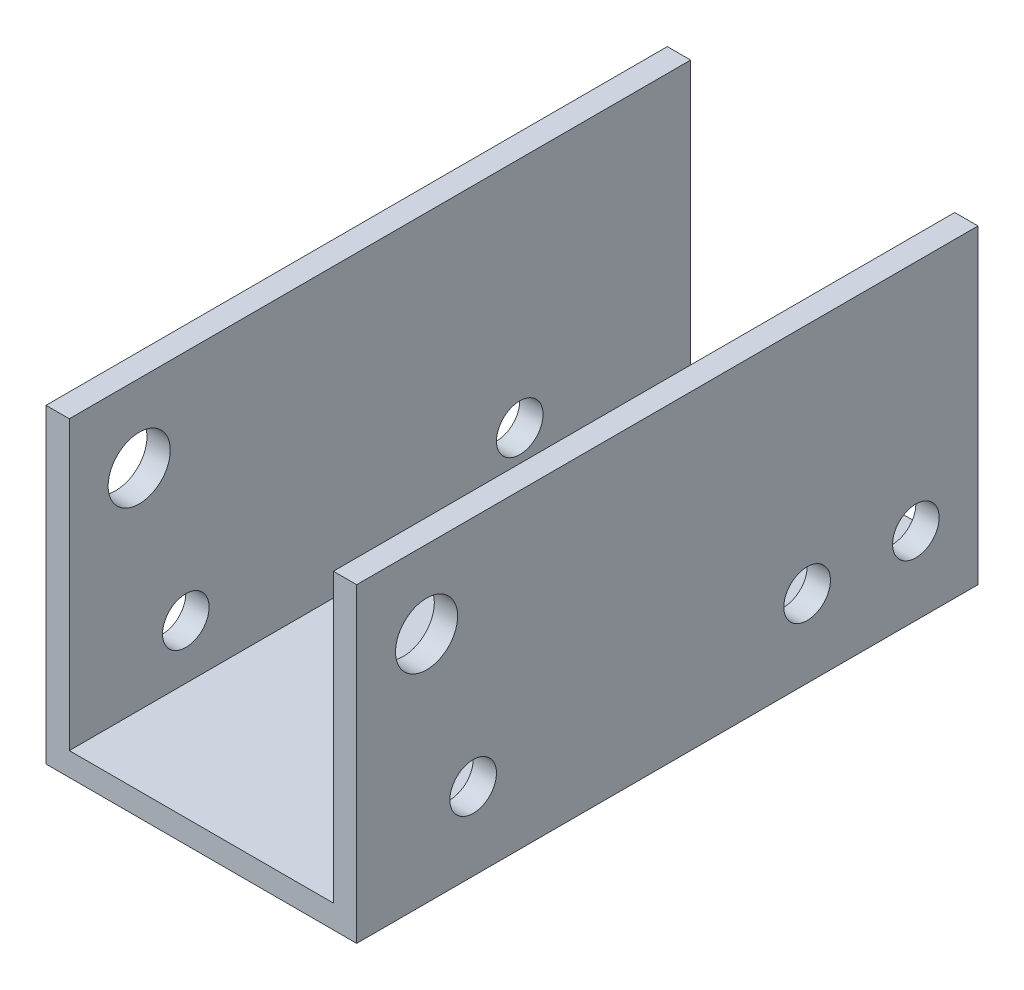
SolidWorks part; units mm, degrees
ref_plane "Plan de face" through (0, 0, 0) normal (0, 0, 1) x (1, 0, 0)
ref_plane "Plan de dessus" through (0, 0, 0) normal (0, 1, 0) x (1, 0, 0)
ref_plane "Plan de droite" through (0, 0, 0) normal (1, 0, 0) x (0, 0, -1)
sketch "Esquisse1" plane through (0, 0, 0) normal (0, 0, 1) x (1, 0, 0)
  line L0 (-8.9048, 18.5) -> (-8.9048, -1.5)
  line L1 (-8.9048, -1.5) -> (11.0952, -1.5)
  line L2 (11.0952, -1.5) -> (11.0952, 18.5)
  line L3 (11.0952, 18.5) -> (9.5952, 18.5)
  line L4 (9.5952, 18.5) -> (9.5952, 0)
  line L5 (9.5952, 0) -> (-7.4048, 0)
  line L6 (-7.4048, 0) -> (-7.4048, 18.5)
  line L7 (-7.4048, 18.5) -> (-8.9048, 18.5)
  dimension "D1" = 1.5
  dimension "D2" = 1.5
  dimension "D3" = 1.5
  dimension "D4" = 20
  dimension "D5" = 20
  dimension "D6" = 20
extrude "Extrusion1" add sketch "Esquisse1" along normal blind 40
sketch "Esquisse2" plane through (11.0952, 0, 0) normal (1, 0, 0) x (0, 0, -1)
  line L0 (-32.5, 3.5) -> (-32.5, 13.5) construction
  line L1 (-40, -1.5) -> (-40, 18.5) construction
  line L2 (-40, -1.5) -> (0, -1.5) construction
  line L3 (0, -1.5) -> (0, 18.5) construction
  circle A0 centre (-32.5, 3.5) radius 1.5
  circle A1 centre (-11, 3.5) radius 1.5
  circle A2 centre (-35.5, 13.5) radius 2
  dimension "D1" = 7.5
  dimension "D4" = 11
  dimension "D2" = 5
  dimension "D3" = 10
  dimension "D5" = 10
  dimension "D6" = 3
extrude "Extrusion2" cut sketch "Esquisse2" against normal through all
sketch "Esquisse3" plane through (11.0952, 0, 0) normal (1, 0, 0) x (0, 0, -1)
  line L0 (-40, -1.5) -> (0, -1.5) construction
  line L1 (0, -1.5) -> (0, 18.5) construction
  circle A0 centre (-4, 3.5) radius 1.5
  dimension "D1" = 5
  dimension "D2" = 4
extrude "Extrusion3" cut sketch "Esquisse3" against normal blind 6
